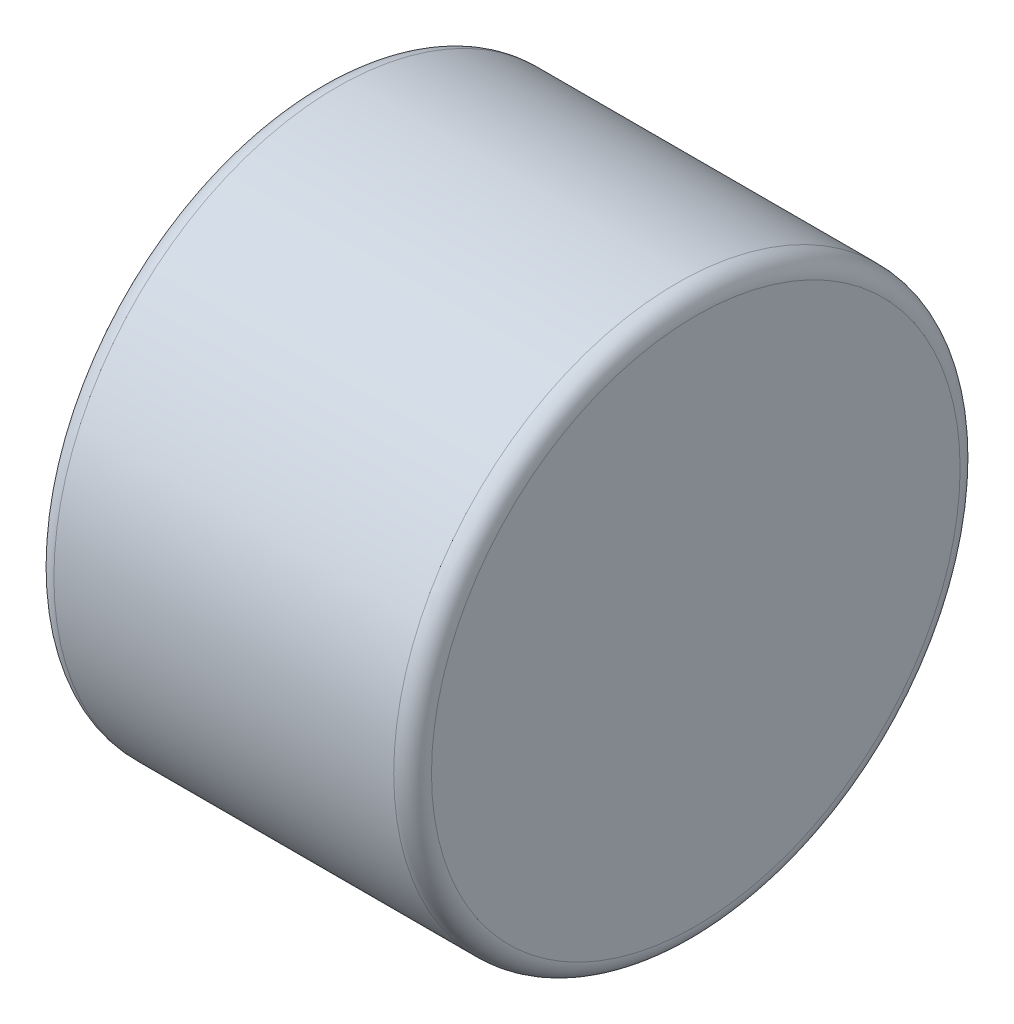
SolidWorks part; units mm, degrees
ref_plane "Front" through (0, 0, 0) normal (0, 0, 1) x (1, 0, 0)
ref_plane "Top" through (0, 0, 0) normal (0, 1, 0) x (1, 0, 0)
ref_plane "Right" through (0, 0, 0) normal (1, 0, 0) x (0, 0, -1)
sketch "Sketch1" plane through (0, 0, 0) normal (1, 0, 0) x (0, 0, -1)
  circle A0 centre (0, 0) radius 3
  dimension "D1" = 6
extrude "Boss-Extrude1" add sketch "Sketch1" along normal blind 4
fillet "Fillet1" radius 0.2 2 edges at (0, 0, -3) (4, 0, -3)
